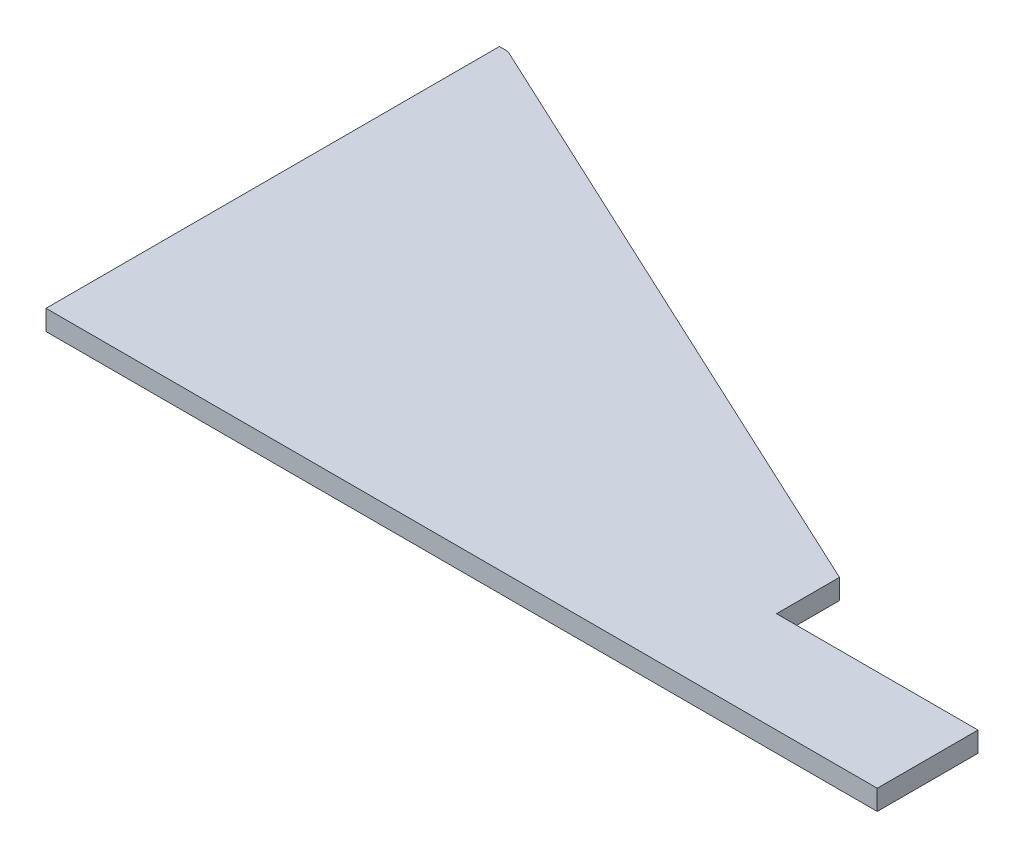
SolidWorks part; units mm, degrees
ref_plane "Front Plane" through (0, 0, 0) normal (0, 0, 1) x (1, 0, 0)
ref_plane "Top Plane" through (0, 0, 0) normal (0, 1, 0) x (1, 0, 0)
ref_plane "Right Plane" through (0, 0, 0) normal (1, 0, 0) x (0, 0, -1)
sketch "Sketch1" plane through (0, 0, 0) normal (0, 1, 0) x (1, 0, 0)
  line L0 (0, 0) -> (330, 0)
  line L1 (330, 0) -> (330, 40)
  line L2 (330, 40) -> (250, 40)
  line L3 (250, 40) -> (250, 65)
  line L4 (250, 65) -> (3.3817, 180)
  line L5 (3.3817, 180) -> (0, 180)
  line L6 (0, 180) -> (0, 0)
  dimension "D1" = 330
  dimension "D2" = 180
  dimension "D3" = 40
  dimension "D4" = 25
  dimension "D5" = 80
  dimension "D6" = 25
extrude "Boss-Extrude1" add sketch "Sketch1" along normal blind 8
